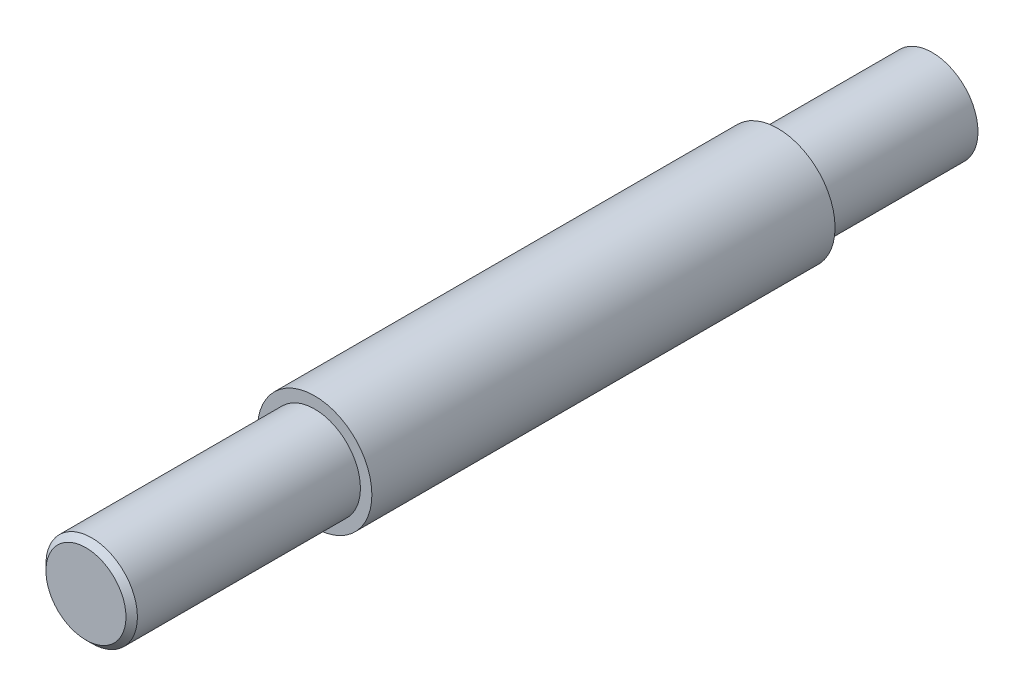
SolidWorks part; units mm, degrees
ref_plane "Alzado" through (0, 0, 0) normal (0, 0, 1) x (1, 0, 0)
ref_plane "Planta" through (0, 0, 0) normal (0, 1, 0) x (1, 0, 0)
ref_plane "Vista lateral" through (0, 0, 0) normal (1, 0, 0) x (0, 0, -1)
sketch "Croquis1" plane through (0, 0, 0) normal (0, 0, 1) x (1, 0, 0)
  circle A0 centre (0, 0) radius 8
  dimension "D1" = 16
extrude "Saliente-Extruir1" add sketch "Croquis1" along normal blind 27
sketch "Croquis2" plane through (0, 0, 27) normal (0, 0, 1) x (1, 0, 0)
  circle A0 centre (0, 0) radius 10
  dimension "D1" = 20
extrude "Saliente-Extruir2" add sketch "Croquis2" along normal blind 81
sketch "Croquis3" plane through (0, 0, 108) normal (0, 0, 1) x (1, 0, 0)
  circle A0 centre (0, 0) radius 8
  dimension "D1" = 16
extrude "Saliente-Extruir3" add sketch "Croquis3" along normal blind 40
chamfer "Chaflán1" distance 1 angle 45 1 edges at (8, 0, 148)
sketch "Croquis4" plane through (0, 0, 0) normal (0, 0, -1) x (-1, 0, 0)
  circle A0 centre (0, 0) radius 4
  dimension "D1" = 8
extrude "Cortar-Extruir1" cut sketch "Croquis4" against normal blind 25
